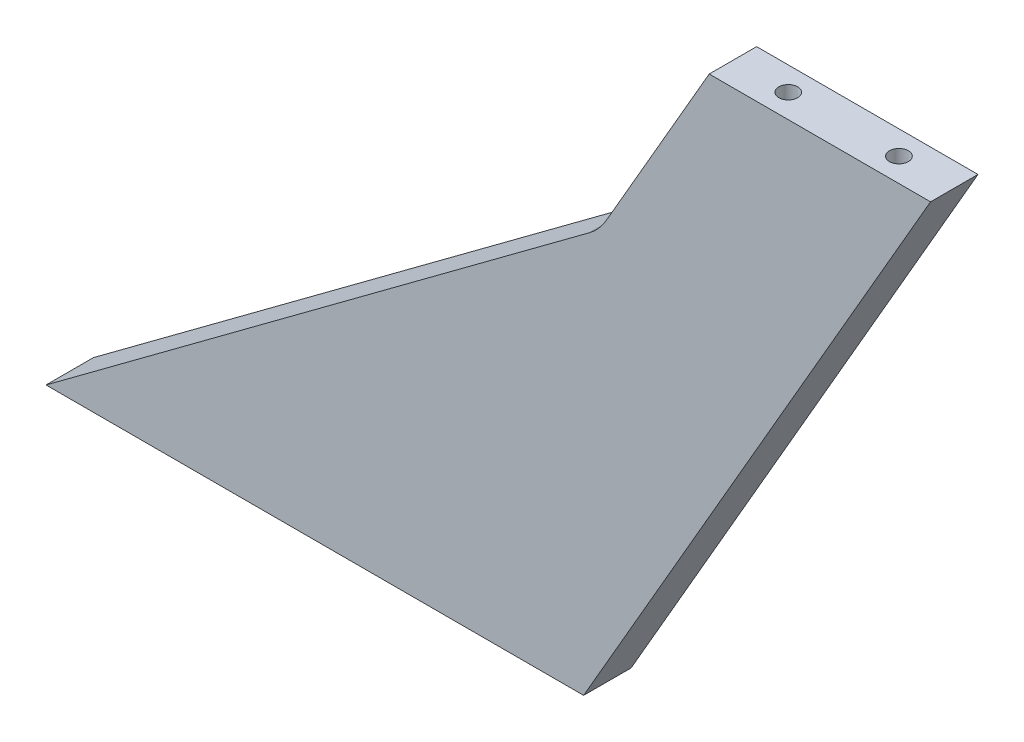
SolidWorks part; units mm, degrees
ref_plane "Front Plane" through (0, 0, 0) normal (0, 0, 1) x (1, 0, 0)
ref_plane "Top Plane" through (0, 0, 0) normal (0, 1, 0) x (1, 0, 0)
ref_plane "Right Plane" through (0, 0, 0) normal (1, 0, 0) x (0, 0, -1)
sketch "Sketch1" plane through (0, 0, 0) normal (0, 1, 0) x (1, 0, 0)
  line L1 (-22.225, 4.7625) -> (22.225, 4.7625)
  line L2 (-22.225, 4.7625) -> (-22.225, -4.7625)
  line L3 (-22.225, -4.7625) -> (22.225, -4.7625)
  line L4 (22.225, 4.7625) -> (22.225, -4.7625)
  point P4 (-22.225, 0)
  point P5 (0, 4.7625)
  dimension "D1" = 9.525
  dimension "D2" = 44.45
sketch "Sketch2" plane through (0, 0, 0) normal (0, 0, 1) x (1, 0, 0)
  line L0 (-22.225, 0) -> (22.225, 0) construction
  line L1 (-22.225, 0) -> (22.225, 0) construction
  line L2 (-22.225, 0) -> (47.4323, 120.65)
  dimension "D1" = 60
  dimension "D2" = 120.65
sweep "Sweep1" add profiles "Sketch1" path "Sketch2"
sketch "Sketch3" plane through (0, 0, 0) normal (0, -1, 0) x (-1, 0, 0)
  line L0 (22.225, 0) -> (-22.225, 0) construction
  line L1 (22.225, 4.7625) -> (22.225, -4.7625) construction
  line L2 (-22.225, -4.7625) -> (-22.225, 4.7625) construction
  line L3 (0, -4.7625) -> (0, 4.7625) construction
  line L4 (22.225, -4.7625) -> (-22.225, -4.7625) construction
  line L5 (-22.225, 4.7625) -> (22.225, 4.7625) construction
  point P12 (11.1125, 0)
  point P13 (-11.1125, 0)
  dimension "D1" = 22.225
  dimension "D2" = 11.1125
hole_wizard "#10-24 Tapped Hole1" positions "Sketch4" profile "Sketch5" tap size "#10-24" standard "ANSI Inch"
sketch "Sketch4" plane through (0, 0, 0) normal (0, -1, 0) x (-1, 0, 0)
  line L0 (-11.1125, 0) -> (11.1125, 0) construction
  point P0 (11.1125, 0)
  point P3 (-11.1125, 0)
sketch "Sketch5" plane through (-11.1125, 0, 0) normal (1, 0, 0) x (0, 0, -1)
  line L0 (0, 0) -> (0, 12.954)
  line L1 (0, 12.954) -> (1.8986, 12.954)
  line L2 (1.8986, 12.954) -> (1.8986, 0)
  line L5 (1.8986, 0) -> (0, 0)
  line L10 (0, 12.954) -> (-1.8987, 12.954) construction
  line L11 (0, -6.35) -> (0, 107.95) construction
  dimension "Tap Drill Dia." = 3.7973
  dimension "Tap Drill Depth" = 12.954
  dimension "Drill Angle" = 180
cosmetic thread "Hole Thread1" parameters "D1"=12.954, "D2"=4.826
cosmetic thread "Hole Thread2" parameters "D1"=12.954, "D2"=4.826
sketch "Sketch11" plane through (0, 120.65, 0) normal (0, 1, 0) x (1, 0, 0)
  line L0 (69.6573, 4.7625) -> (69.6573, -4.7625) construction
  line L1 (91.8823, 4.7625) -> (47.4323, 4.7625) construction
  line L2 (47.4323, -4.7625) -> (91.8823, -4.7625) construction
  line L3 (47.4323, 0) -> (91.8823, 0) construction
  line L4 (47.4323, 4.7625) -> (47.4323, -4.7625) construction
  line L5 (91.8823, -4.7625) -> (91.8823, 4.7625) construction
  point P0 (58.5448, 0)
  point P1 (80.7698, 0)
  point P17 (69.6573, 0)
  dimension "D1" = 22.225
  dimension "D2" = 11.1125
hole_wizard "#10-24 Tapped Hole2" positions "Sketch12" profile "Sketch13" tap size "#10-24" standard "ANSI Inch"
sketch "Sketch12" plane through (0, 120.65, 0) normal (0, 1, 0) x (1, 0, 0)
  point P0 (58.5448, 0)
  point P3 (80.7698, 0)
sketch "Sketch13" plane through (58.5448, 120.65, 0) normal (1, 0, 0) x (0, 0, 1)
  line L0 (0, 0) -> (0, 9.652)
  line L1 (0, 9.652) -> (1.8986, 9.652)
  line L2 (1.8986, 9.652) -> (1.8986, 0)
  line L5 (1.8986, 0) -> (0, 0)
  line L10 (0, 9.652) -> (-1.8987, 9.652) construction
  line L11 (0, -6.35) -> (0, 107.95) construction
  dimension "Tap Drill Dia." = 3.7973
  dimension "Tap Drill Depth" = 9.652
  dimension "Drill Angle" = 180
cosmetic thread "Hole Thread3" parameters "D1"=9.652, "D2"=4.826
cosmetic thread "Hole Thread4" parameters "D1"=9.652, "D2"=4.826
sketch "Sketch14" plane through (0, 0, 4.7625) normal (0, 0, 1) x (1, 0, 0)
  line L0 (-22.225, 0) -> (-85.725, 0)
  line L1 (-85.725, 0) -> (25.4353, 82.55)
  line L2 (-22.225, 0) -> (47.4323, 120.65) construction
  line L3 (25.4353, 82.55) -> (-22.225, 0)
  point P7 (23.2586, 78.7799)
  point P8 (0, 0)
  point P9 (0, 0)
  dimension "D1" = 63.5
  dimension "D2" = 82.55
extrude "Boss-Extrude1" add sketch "Sketch14" against normal up to surface (9.525 mm away) up to face at (34.8287, 60.325, -4.7625)
sketch "Sketch15" plane through (0, 0, 0) normal (0, -1, 0) x (1, 0, 0)
  point P0 (-65.0875, 0)
  point P1 (-42.8625, 0)
  dimension "D1" = 31.75
  dimension "D2" = 22.225
hole_wizard "#10-24 Tapped Hole3" positions "Sketch16" profile "Sketch17" tap size "#10-24" standard "ANSI Inch"
sketch "Sketch16" plane through (0, 0, 0) normal (0, -1, 0) x (-1, 0, 0)
  point P0 (42.8625, 0)
  point P3 (65.0875, 0)
sketch "Sketch17" plane through (-42.8625, 0, 0) normal (1, 0, 0) x (0, 0, -1)
  line L0 (0, 0) -> (0, 14.0948)
  line L1 (0, 14.0948) -> (1.8986, 12.954)
  line L2 (1.8986, 12.954) -> (1.8986, 0)
  line L5 (1.8986, 0) -> (0, 0)
  line L10 (0, 14.0948) -> (-1.8986, 12.954) construction
  line L11 (0, -6.35) -> (0, 107.95) construction
  dimension "Tap Drill Dia." = 3.7973
  dimension "Tap Drill Depth" = 12.954
  dimension "Drill Angle" = 118
cosmetic thread "Hole Thread5" parameters "D1"=9.652, "D2"=4.826
cosmetic thread "Hole Thread6" parameters "D1"=9.652, "D2"=4.826
fillet "Fillet1" radius 12.7 1 edges at (25.4353, 82.55, 0)
